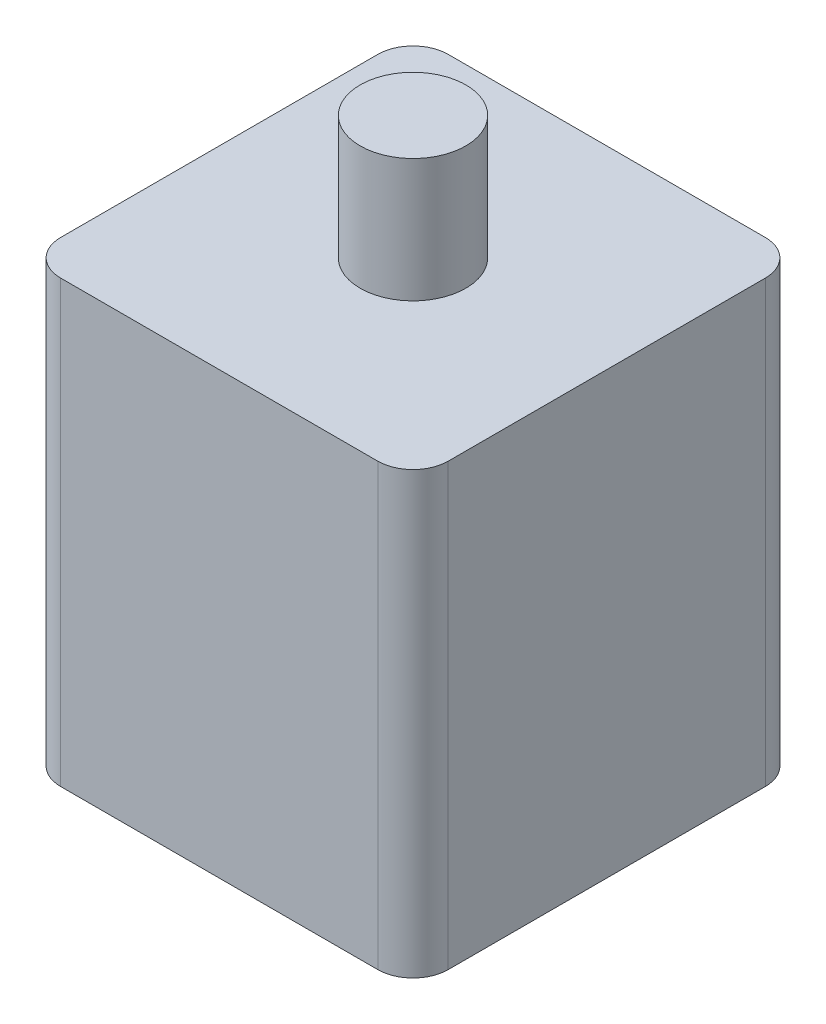
SolidWorks part; units mm, degrees
ref_plane "Front Plane" through (0, 0, 0) normal (0, 0, 1) x (1, 0, 0)
ref_plane "Top Plane" through (0, 0, 0) normal (0, 1, 0) x (1, 0, 0)
ref_plane "Right Plane" through (0, 0, 0) normal (1, 0, 0) x (0, 0, -1)
sketch "Sketch1" plane through (0, 0, 0) normal (0, 1, 0) x (1, 0, 0)
  line L1 (-9, -11) -> (9, -11)
  line L2 (-11, -9) -> (-11, 9)
  line L3 (-9, 11) -> (9, 11)
  line L4 (11, -9) -> (11, 9)
  line L5 (-11, -11) -> (11, 11) construction
  line L6 (-11, 11) -> (11, -11) construction
  circle A1 centre (0, 0) radius 6
  arc A2 (9, -11) -> (11, -9) centre (9, -9) ccw
  arc A3 (-9, -11) -> (-11, -9) centre (-9, -9) cw
  arc A4 (9, 11) -> (11, 9) centre (9, 9) cw
  arc A5 (-11, 9) -> (-9, 11) centre (-9, 9) cw
  dimension "D1" = 12
  dimension "D4" = 2
  dimension "D2" = 22
  dimension "D3" = 22
extrude "Boss-Extrude1" add sketch "Sketch1" along normal blind 25 contours A1 | A5 L2 A3 L1 A2 L4 A4 L3 A1
sketch "Sketch2" plane through (0, 25, 0) normal (0, 1, 0) x (1, 0, 0)
  circle A0 centre (0, 0) radius 3
  dimension "D1" = 6
extrude "Boss-Extrude2" add sketch "Sketch2" along normal blind 7
scale "Scale1" scale about centroid uniform scaling yes scale factor 0.7
